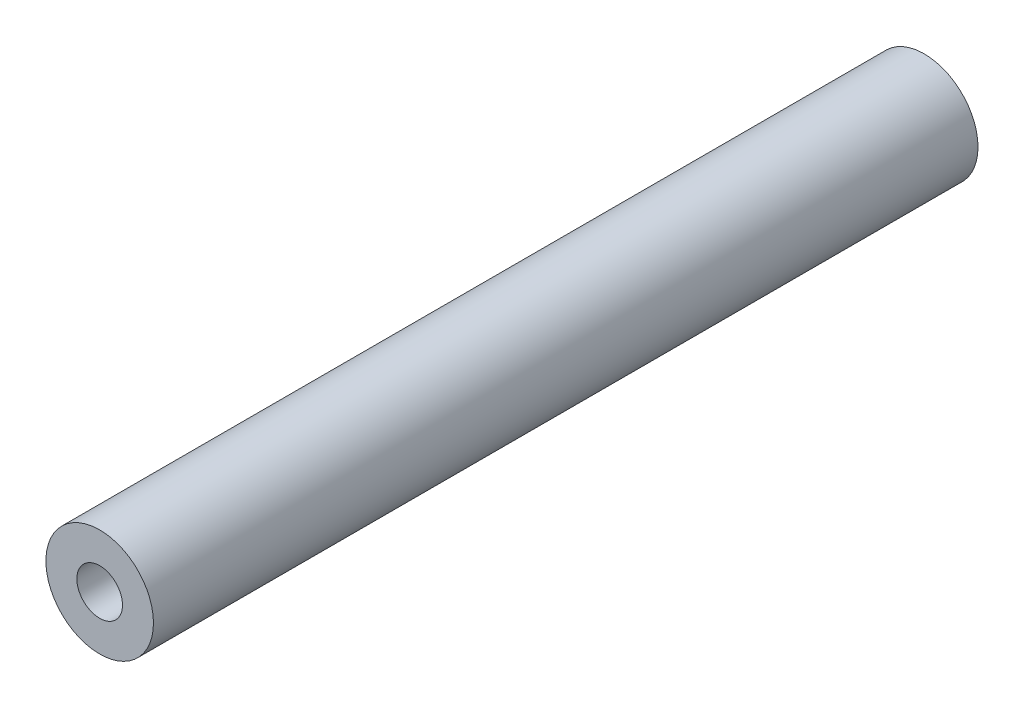
SolidWorks part; units mm, degrees
ref_plane "Front Plane" through (0, 0, 0) normal (0, 0, 1) x (1, 0, 0)
ref_plane "Top Plane" through (0, 0, 0) normal (0, 1, 0) x (1, 0, 0)
ref_plane "Right Plane" through (0, 0, 0) normal (1, 0, 0) x (0, 0, -1)
sketch "Sketch1" plane through (0, 0, 0) normal (0, 0, 1) x (1, 0, 0)
  circle A0 centre (0, 0) radius 4.7625
  dimension "D2" = 9.525
extrude "Boss-Extrude1" add sketch "Sketch1" along normal mid plane 73.025
hole_wizard "#10-32 Tapped Hole2" positions "3DSketch4" profile "Sketch5" tap size "#10-32" standard "ANSI Inch"
sketch3d "3DSketch4"
  line L0 (0, 0, 36.5125) -> (0, 0, -36.5125) construction
  point P0 (0, 0, -36.5125)
  point P4 (0, 0, 36.5125)
sketch "Sketch5" plane through (0, 0, -36.5125) normal (1, 0, 0) x (0, 1, 0)
  line L0 (0, 0) -> (0, 13.2428)
  line L1 (0, 13.2428) -> (2.0193, 12.0294)
  line L2 (2.0193, 12.0294) -> (2.0193, 0)
  line L5 (2.0193, 0) -> (0, 0)
  line L10 (0, 13.2428) -> (-2.0193, 12.0294) construction
  line L11 (0, -6.35) -> (0, 107.95) construction
  dimension "Tap Drill Dia." = 4.0386
  dimension "Tap Drill Depth" = 12.0294
  dimension "Drill Angle" = 118
cosmetic thread "Hole Thread3" parameters "D1"=9.652, "D2"=4.826
cosmetic thread "Hole Thread4" parameters "D1"=9.652, "D2"=4.826
